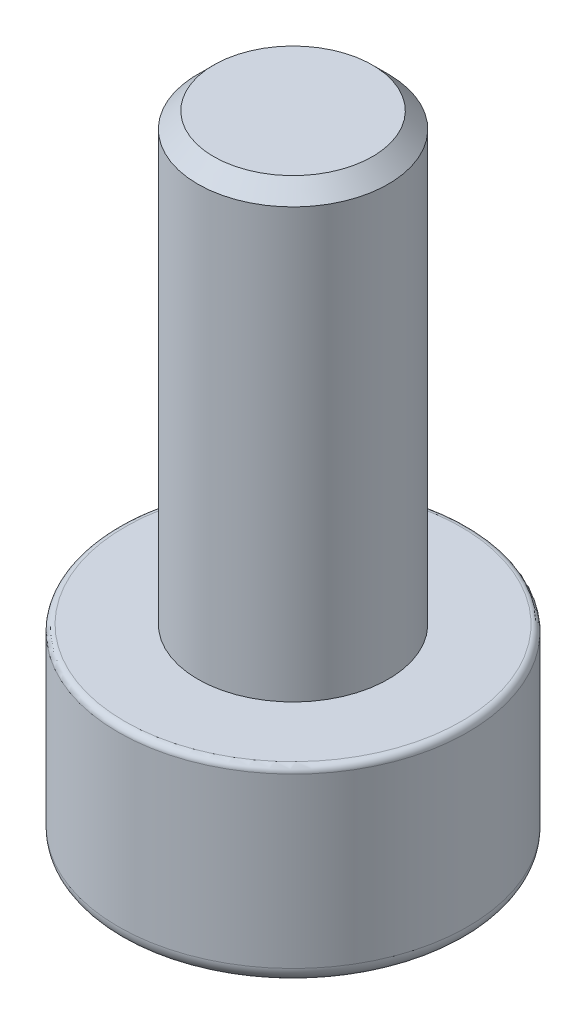
SolidWorks part; units mm, degrees
ref_plane "Front Plane" through (0, 0, 0) normal (0, 0, 1) x (1, 0, 0)
ref_plane "Top Plane" through (0, 0, 0) normal (0, 1, 0) x (1, 0, 0)
ref_plane "Right Plane" through (0, 0, 0) normal (1, 0, 0) x (0, 0, -1)
sketch "Sketch1" plane through (0, 0, 0) normal (0, 1, 0) x (1, 0, 0)
  circle A0 centre (0, 0) radius 2.75
  dimension "D1" = 5.5
extrude "Boss-Extrude1" add sketch "Sketch1" along normal blind 3
sketch "Sketch2" plane through (0, 3, 0) normal (0, 1, 0) x (1, 0, 0)
  circle A0 centre (0, 0) radius 1.5
  dimension "D1" = 3
extrude "Boss-Extrude2" add sketch "Sketch2" along normal blind 7 contours A0
sketch "Sketch3" plane through (0, 0, 0) normal (0, -1, 0) x (1, 0, 0)
  line L1 (0.9342, 0.9746) -> (-0.3769, 1.2963)
  line L2 (-0.3769, 1.2963) -> (-1.3111, 0.3217)
  line L3 (-1.3111, 0.3217) -> (-0.9342, -0.9746)
  line L4 (-0.9342, -0.9746) -> (0.3769, -1.2963)
  line L5 (0.3769, -1.2963) -> (1.3111, -0.3217)
  line L6 (1.3111, -0.3217) -> (0.9342, 0.9746)
  circle A0 centre (0, 0) radius 1.1691 construction
  dimension "D1" = 2.7
extrude "Cut-Extrude1" cut sketch "Sketch3" against normal blind 1.5
chamfer "Chamfer1" distance 0.25 distance2 0.25 6 edges at (-0.2786, 0, -1.1355) (-1.1226, 0, -0.3264) (-0.844, 0, 0.809) (0.2786, 0, 1.1355) (1.1226, 0, 0.3264) (0.844, 0, -0.809)
fillet "Fillet1" radius 0.25 1 edges at (0, 0, 2.75)
chamfer "Chamfer2" distance 0.25 angle 45 1 edges at (0, 10, 1.5)
fillet "Fillet2" radius 0.1 1 edges at (0, 3, 2.75)
